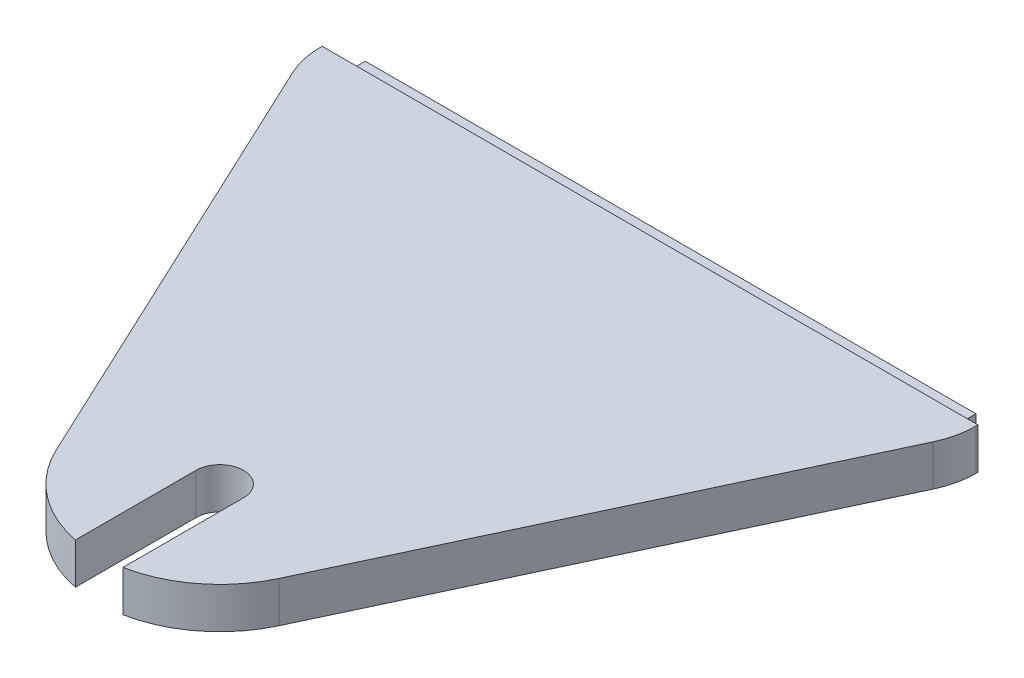
SolidWorks part; units mm, degrees
ref_plane "Front Plane" through (0, 0, 0) normal (0, 0, 1) x (1, 0, 0)
ref_plane "Top Plane" through (0, 0, 0) normal (0, 1, 0) x (1, 0, 0)
ref_plane "Right Plane" through (0, 0, 0) normal (1, 0, 0) x (0, 0, -1)
sketch "Sketch2" plane through (0, 0, 0) normal (0, 1, 0) x (1, 0, 0)
  line L0 (-40, 0) -> (40, 0)
  line L1 (-40, 0) -> (-13.5822, -56.3658)
  line L2 (40, 0) -> (13.5822, -56.3658)
  arc A0 (-13.5822, -56.3658) -> (13.5822, -56.3658) centre (0, -50) ccw
  point P4 (0, 0)
  dimension "D2" = 30
  dimension "D1" = 80
  dimension "D3" = 50
extrude "Boss-Extrude1" add sketch "Sketch2" along normal blind 5 contours L1 A0 L2 L0
sketch "Sketch3" plane through (0, 0, 0) normal (0, 0, -1) x (-1, 0, 0)
  line L1 (-40, 5) -> (40, 5)
  line L2 (-40, 5) -> (-40, 0)
  line L3 (-40, 0) -> (40, 0)
  line L4 (40, 5) -> (40, 0)
extrude "Boss-Extrude2" add sketch "Sketch3" along normal blind 5 contours L1 L4 L3 L2
sketch "Sketch6" plane through (0, 0, -5) normal (0, 0, -1) x (-1, 0, 0)
  line L1 (-40, 5) -> (40, 5)
  line L2 (-40, 5) -> (-40, 0)
  line L3 (-40, 0) -> (40, 0)
  line L4 (40, 5) -> (40, 0)
  line L5 (-37.25, 3.55) -> (37.25, 3.55)
  line L6 (-37.25, 3.55) -> (-37.25, 1.45)
  line L7 (-37.25, 1.45) -> (37.25, 1.45)
  line L8 (37.25, 3.55) -> (37.25, 1.45)
  line L9 (-37.25, 3.55) -> (37.25, 1.45) construction
  line L10 (-37.25, 1.45) -> (37.25, 3.55) construction
  point P6 (0, 2.5)
  dimension "D1" = 74.5
  dimension "D2" = 2.1
  dimension "D3" = 0
  dimension "D4" = 2.5
extrude "Cut-Extrude2" cut sketch "Sketch6" against normal blind 2.5
fillet "Fillet1" radius 10 2 edges at (-40, 2.5, 0) (40, 2.5, 0)
sketch "Sketch7" plane through (0, 0, 0) normal (0, -1, 0) x (-1, 0, 0)
  line L0 (2.9, -50) -> (2.9, -64.717)
  line L1 (-2.9, -50) -> (-2.9, -64.717)
  arc A0 (2.9, -50) -> (-2.9, -50) centre (0, -50) ccw
  arc A1 (-2.9, -64.717) -> (2.9, -64.717) centre (0, -50) ccw
  dimension "D1" = 5.8
  dimension "D2" = 30
extrude "Cut-Extrude3" cut sketch "Sketch7" against normal blind 5
